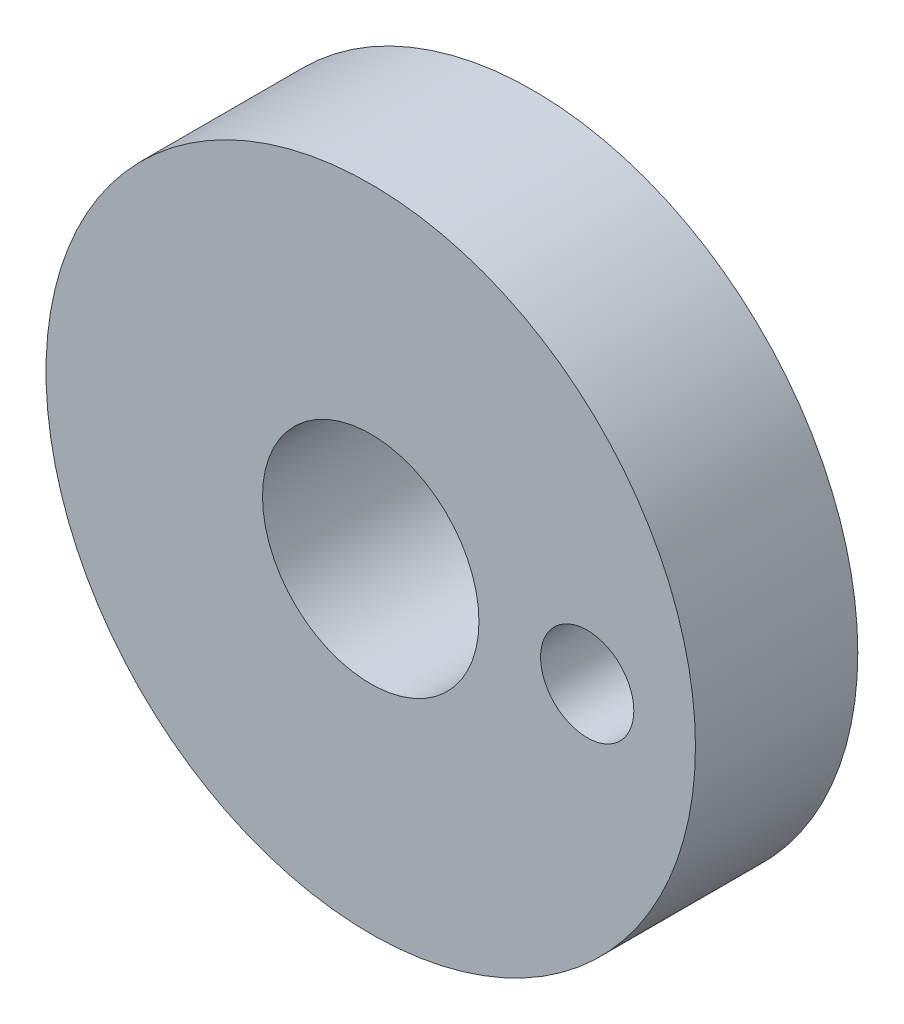
SolidWorks part; units mm, degrees
ref_plane "Front Plane" through (0, 0, 0) normal (0, 0, 1) x (1, 0, 0)
ref_plane "Top Plane" through (0, 0, 0) normal (0, 1, 0) x (1, 0, 0)
ref_plane "Right Plane" through (0, 0, 0) normal (1, 0, 0) x (0, 0, -1)
sketch "Sketch1" plane through (0, 0, 0) normal (0, 0, 1) x (1, 0, 0)
  circle A0 centre (0, 0) radius 30
  circle A1 centre (20, 0) radius 4.3056
  circle A2 centre (0, 0) radius 10
  dimension "D1" = 60
  dimension "D3" = 20
  dimension "D2" = 20
extrude "Boss-Extrude1" add sketch "Sketch1" along normal blind 15
